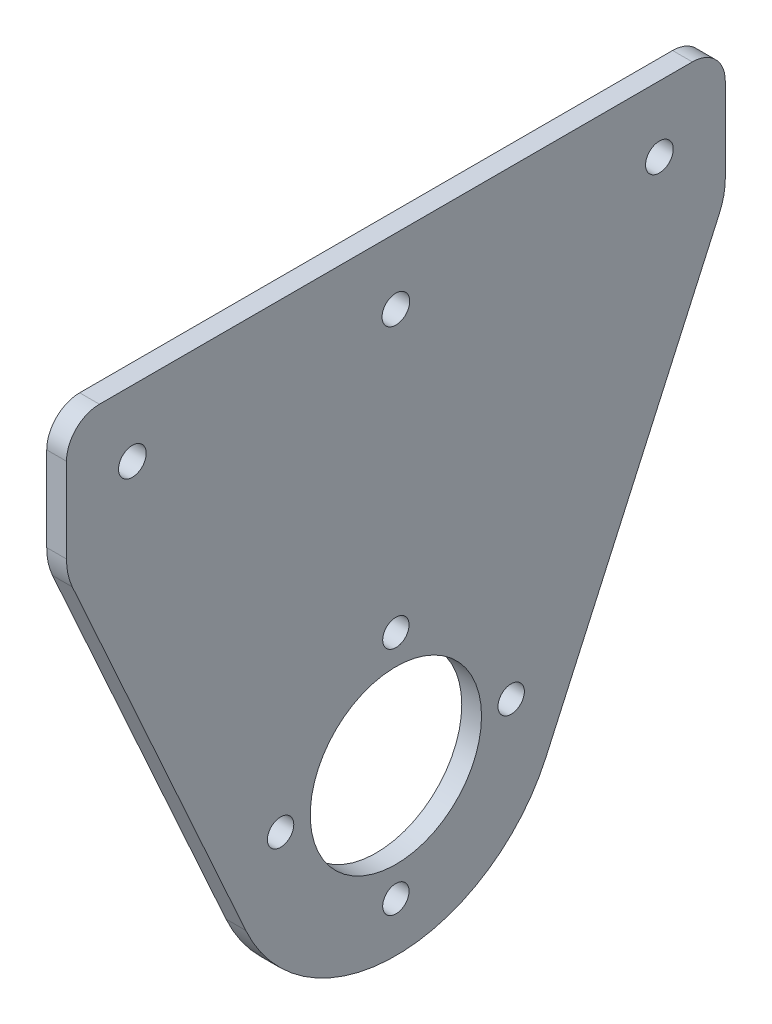
SolidWorks part; units mm, degrees
ref_plane "前视基准面" through (0, 0, 0) normal (0, 0, 1) x (1, 0, 0)
ref_plane "上视基准面" through (0, 0, 0) normal (0, 1, 0) x (1, 0, 0)
ref_plane "右视基准面" through (0, 0, 0) normal (1, 0, 0) x (0, 0, -1)
other "Configuration Table"
sketch "草图1" plane through (0, 0, 0) normal (1, 0, 0) x (0, 0, -1)
  circle A0 centre (0, 0) radius 13
  circle A1 centre (0, 0) radius 25
  dimension "D1" = 26
  dimension "D2" = 50
extrude "凸台-拉伸1" add sketch "草图1" along normal blind 3
sketch "草图2" plane through (3, 0, 0) normal (1, 0, 0) x (0, 0, -1)
  circle A0 centre (0, 0) radius 17.5 construction
  circle A1 centre (0, 17.5) radius 2
  circle A2 centre (17.5, 0) radius 2
  circle A3 centre (0, -17.5) radius 2
  circle A4 centre (-17.5, 0) radius 2
  point P14 (0, 0)
  dimension "D1" = 35
  dimension "D2" = 4
  dimension "D3" = 4
extrude "切除-拉伸1" cut sketch "草图2" against normal blind 3
sketch "草图3" plane through (3, 0, 0) normal (1, 0, 0) x (0, 0, -1)
  line L0 (-25, 0) -> (-25, 70)
  line L1 (-25, 70) -> (25, 70)
  line L2 (25, 70) -> (25, 0)
  circle A0 centre (0, 0) radius 25 construction
  circle A2 centre (0, 0) radius 25
  arc A3 (25, 0) -> (-25, 0) centre (0, 0) ccw
  dimension "D1" = 0
  dimension "D2" = 70
extrude "凸台-拉伸2" add sketch "草图3" against normal blind 3
sketch "草图4" plane through (3, 0, 0) normal (1, 0, 0) x (0, 0, -1)
  line L0 (25, 70) -> (-25, 70) construction
  line L1 (-50, 70) -> (50, 70)
  line L2 (-50, 70) -> (-50, 50)
  line L3 (-50, 50) -> (50, 50)
  line L4 (50, 70) -> (50, 50)
  line L5 (0, 50) -> (0, 0) construction
  dimension "D1" = 20
  dimension "D2" = 100
extrude "凸台-拉伸3" add sketch "草图4" against normal blind 3
sketch "草图5" plane through (3, 0, 0) normal (1, 0, 0) x (0, 0, -1)
  line L0 (-22.7859, -10.2859) -> (-50, 50)
  line L1 (22.7859, -10.2859) -> (50, 50)
  line L9 (25, 0) -> (25, 50)
  line L10 (25, 50) -> (50, 50)
  line L11 (50, 50) -> (50, 70)
  line L12 (50, 70) -> (-50, 70)
  line L13 (-50, 70) -> (-50, 50)
  line L14 (-50, 50) -> (-25, 50)
  line L15 (-25, 50) -> (-25, 0)
  line L16 (25, 0) -> (25, 50)
  line L17 (25, 50) -> (50, 50)
  line L21 (-50, 50) -> (-25, 50)
  line L22 (-25, 50) -> (-25, 0)
  arc A0 (-25, 0) -> (25, 0) centre (0, 0) ccw construction
  arc A1 (22.7859, -10.2859) -> (25, 0) centre (0, 0) ccw
  arc A2 (-25, 0) -> (25, 0) centre (0, 0) ccw
  arc A3 (-25, 0) -> (-22.7859, -10.2859) centre (0, 0) ccw
  dimension "D1" = 0
extrude "凸台-拉伸4" add sketch "草图5" against normal blind 3
sketch "草图6" plane through (3, 0, 0) normal (1, 0, 0) x (0, 0, -1)
  line L0 (-50, 60) -> (50, 60) construction
  line L1 (-50, 70) -> (-50, 50) construction
  line L2 (50, 50) -> (50, 70) construction
  circle A0 centre (-40, 60) radius 2.1
  circle A1 centre (0, 60) radius 2.1
  circle A2 centre (40, 60) radius 2.1
  dimension "D1" = 4.2
  dimension "D2" = 10
  dimension "D4" = 40
  dimension "D3" = 3
extrude "切除-拉伸2" cut sketch "草图6" against normal through all
fillet "圆角1" radius 5 2 edges at (1.5, 70, -50) (1.5, 70, 50)
fillet "圆角2" radius 10 2 edges at (1.5, 50, -50) (1.5, 50, 50)
